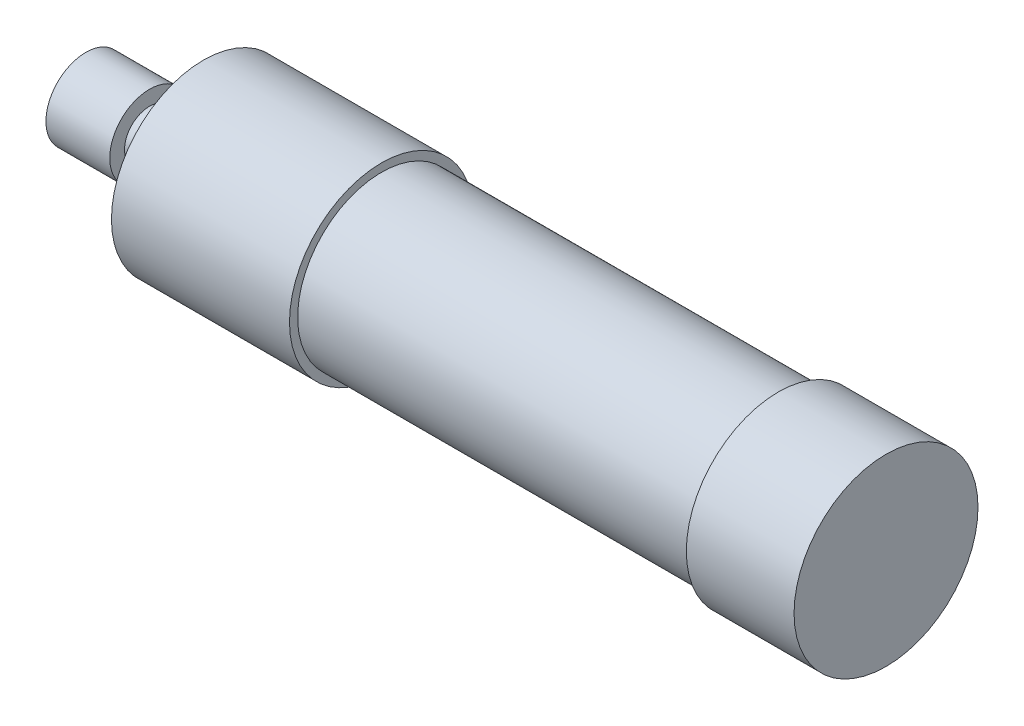
SolidWorks part; units mm, degrees
ref_plane "Front Plane" through (0, 0, 0) normal (0, 0, 1) x (1, 0, 0)
ref_plane "Top Plane" through (0, 0, 0) normal (0, 1, 0) x (1, 0, 0)
ref_plane "Right Plane" through (0, 0, 0) normal (1, 0, 0) x (0, 0, -1)
sketch "Sketch1" plane through (0, 0, 0) normal (0, 0, 1) x (1, 0, 0)
  line L0 (0, 0) -> (-95.584, 0) construction
  line L1 (-95.584, 0) -> (-95.584, 4.7625)
  line L2 (-95.584, 4.7625) -> (-87.964, 4.7625)
  line L3 (-87.964, 4.7625) -> (-87.964, 2.9972)
  line L4 (-87.964, 2.9972) -> (-84.7901, 2.9972)
  line L5 (-84.7901, 2.9972) -> (-84.7901, 6.0071)
  line L6 (-84.7901, 6.0071) -> (-81.534, 6.0071)
  line L7 (-81.534, 6.0071) -> (-81.534, 10.9855)
  line L8 (-81.534, 10.9855) -> (-60.2691, 10.9855)
  line L9 (-60.2691, 10.9855) -> (-60.2691, 10.013)
  line L10 (-60.2691, 10.013) -> (-12.8696, 10.013)
  line L11 (-12.8696, 10.013) -> (-12.8696, 10.9855)
  line L12 (-12.8696, 10.9855) -> (0, 10.9855)
  line L13 (0, 10.9855) -> (0, 0)
  line L14 (0, 0) -> (-95.584, 0)
  point P12 (-87.8744, 0)
  point P16 (-85.7455, 4.7625)
  point P17 (-104.3139, 0)
  point P18 (-12.8696, 8.7187)
  point P19 (-60.2691, 8.9533)
  point P20 (-99.9251, 0)
  point P21 (0, 0)
  point P22 (-84.7901, 2.9972)
  point P23 (-95.584, 0)
  dimension "D1" = 9.525
  dimension "D2" = 81.534
  dimension "D3" = 21.971
  dimension "D4" = 12.0142
  dimension "D5" = 7.62
  dimension "D6" = 5.9944
revolve "Revolve1" add sketch "Sketch1" angle 360 about L0
hole_wizard "M3x0.5 Tapped Hole1" positions "Sketch2" profile "Sketch3" tap size "M3x0.5" standard "ANSI Metric"
sketch "Sketch2" plane through (-81.534, 0, 0) normal (-1, 0, 0) x (0, 0, 1)
  point P0 (0, 9)
  point P3 (0, 0)
  dimension "D1" = 9
sketch "Sketch3" plane through (-81.534, 9, 0) normal (0, 1, 0) x (0, 0, 1)
  line L0 (0, 0) -> (0, 13.4511)
  line L1 (0, 13.4511) -> (1.25, 12.7)
  line L2 (1.25, 12.7) -> (1.25, 0)
  line L5 (1.25, 0) -> (0, 0)
  line L10 (0, 13.4511) -> (-1.25, 12.7) construction
  line L11 (0, -6.35) -> (0, 107.95) construction
  dimension "Tap Drill Dia." = 2.5
  dimension "Tap Drill Depth" = 12.7
  dimension "Drill Angle" = 118
pattern_circular "CirPattern1" count 4 over 360 about axis through (0, 0, 0) along (1, 0, 0) of "M3x0.5 Tapped Hole1"
